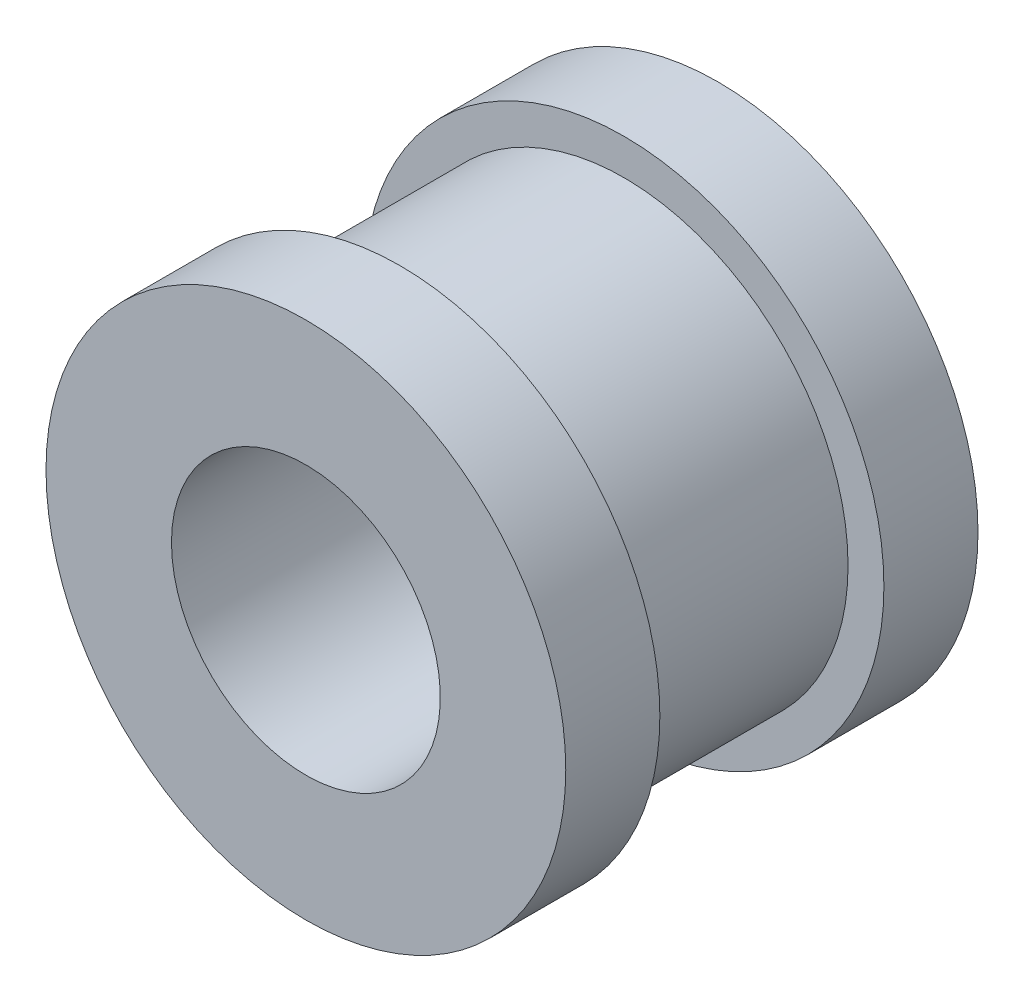
SolidWorks part; units mm, degrees
ref_plane "Front Plane" through (0, 0, 0) normal (0, 0, 1) x (1, 0, 0)
ref_plane "Top Plane" through (0, 0, 0) normal (0, 1, 0) x (1, 0, 0)
ref_plane "Right Plane" through (0, 0, 0) normal (1, 0, 0) x (0, 0, -1)
sketch "Sketch1" plane through (0, 0, 0) normal (0, 0, 1) x (1, 0, 0)
  circle A0 centre (0, 0) radius 2.9
  dimension "D1" = 5.8
extrude "Boss-Extrude1" add sketch "Sketch1" along normal blind 1.05
sketch "Sketch2" plane through (0, 0, 1.05) normal (0, 0, 1) x (1, 0, 0)
  circle A0 centre (0, 0) radius 2.5
  dimension "D1" = 5
extrude "Boss-Extrude2" add sketch "Sketch2" along normal blind 2.5
ref_plane "Plane1" through (0, 0, 2.3) normal (0, 0, 1) x (1, 0, 0)
mirror "Mirror1" about plane through (0, 0, 2.3) normal (0, 0, 1) of "Boss-Extrude1"
sketch "Sketch3" plane through (0, 0, 0) normal (0, 0, -1) x (-1, 0, 0)
  circle A0 centre (0, 0) radius 1.5
  dimension "D1" = 3
extrude "Cut-Extrude1" cut sketch "Sketch3" against normal up to surface (4.6 mm away) up to face at (2.9, 0, 4.6)
